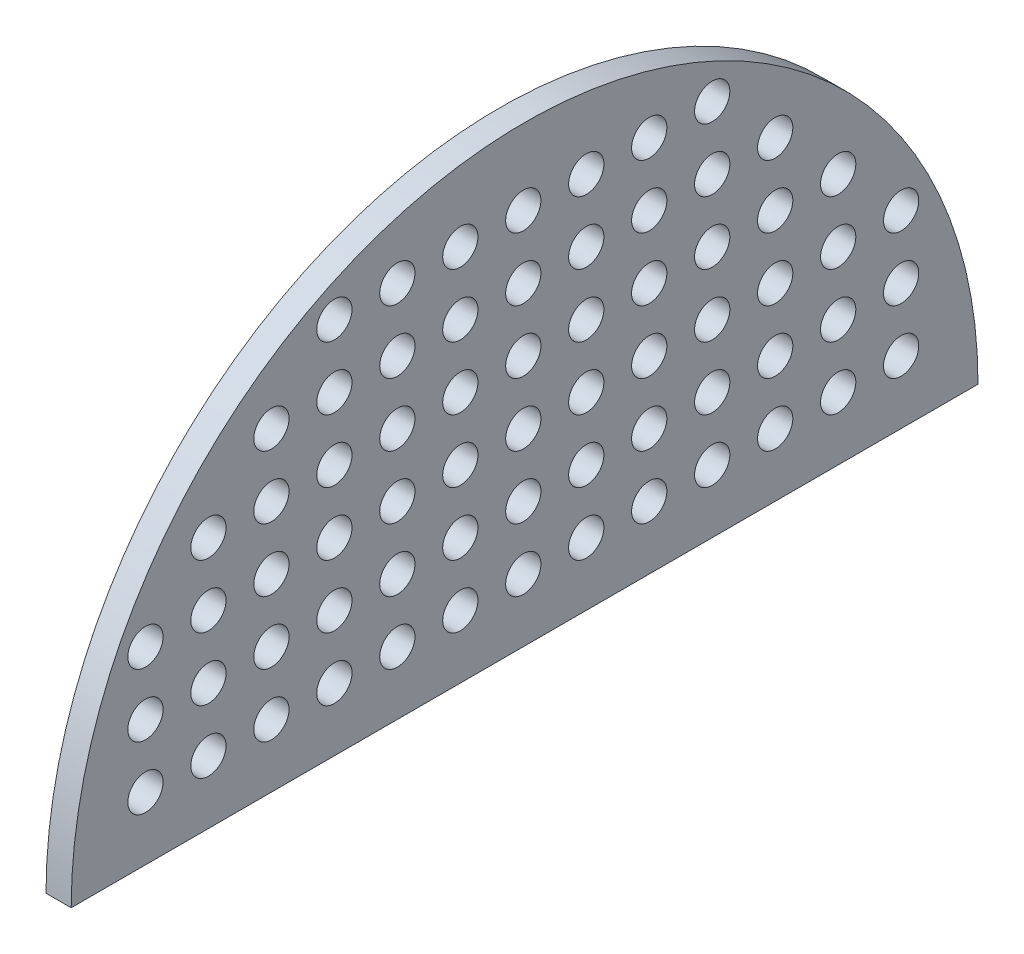
SolidWorks part; units mm, degrees
ref_plane "Front Plane" through (0, 0, 0) normal (0, 0, 1) x (1, 0, 0)
ref_plane "Top Plane" through (0, 0, 0) normal (0, 1, 0) x (1, 0, 0)
ref_plane "Right Plane" through (0, 0, 0) normal (1, 0, 0) x (0, 0, -1)
sketch "Sketch3" plane through (0, 0, 0) normal (1, 0, 0) x (0, 0, -1)
  line L0 (-168.7029, 0) -> (191.2971, 0)
  arc A0 (-168.7029, 0) -> (191.2971, 0) centre (11.2971, 0) cw
  dimension "D1" = 360
extrude "Boss-Extrude2" add sketch "Sketch3" along normal blind 10 contours A0 L0
sketch "Sketch4" plane through (0, 0, 0) normal (-1, 0, 0) x (0, 0, 1)
  line L0 (168.7029, 0) -> (-191.2971, 0) construction
  circle A1 centre (-160.7818, 25) radius 7
  circle A2 centre (-160.7818, 25) radius 10
  circle A3 centre (-135.7818, 25) radius 7
  circle A4 centre (-135.7818, 25) radius 10
  circle A5 centre (-110.7818, 25) radius 7
  circle A6 centre (-110.7818, 25) radius 10
  circle A7 centre (-85.7818, 25) radius 7
  circle A8 centre (-85.7818, 25) radius 10
  circle A9 centre (-60.7818, 25) radius 7
  circle A10 centre (-60.7818, 25) radius 10
  circle A11 centre (-35.7818, 25) radius 7
  circle A12 centre (-35.7818, 25) radius 10
  circle A13 centre (-10.7818, 25) radius 7
  circle A14 centre (-10.7818, 25) radius 10
  circle A15 centre (14.2182, 25) radius 7
  circle A16 centre (14.2182, 25) radius 10
  circle A17 centre (39.2182, 25) radius 7
  circle A18 centre (39.2182, 25) radius 10
  circle A19 centre (64.2182, 25) radius 7
  circle A20 centre (64.2182, 25) radius 10
  circle A21 centre (89.2182, 25) radius 7
  circle A22 centre (89.2182, 25) radius 10
  circle A23 centre (114.2182, 25) radius 7
  circle A24 centre (114.2182, 25) radius 10
  circle A25 centre (139.2182, 25) radius 7
  circle A26 centre (139.2182, 25) radius 10
  circle A27 centre (-135.7818, 50) radius 7
  circle A28 centre (-135.7818, 50) radius 10
  circle A29 centre (-110.7818, 50) radius 7
  circle A30 centre (-110.7818, 50) radius 10
  circle A31 centre (-85.7818, 50) radius 7
  circle A32 centre (-85.7818, 50) radius 10
  circle A33 centre (-60.7818, 50) radius 7
  circle A34 centre (-60.7818, 50) radius 10
  circle A35 centre (-35.7818, 50) radius 7
  circle A36 centre (-35.7818, 50) radius 10
  circle A37 centre (-10.7818, 50) radius 7
  circle A38 centre (-10.7818, 50) radius 10
  circle A39 centre (14.2182, 50) radius 7
  circle A40 centre (14.2182, 50) radius 10
  circle A41 centre (39.2182, 50) radius 7
  circle A42 centre (39.2182, 50) radius 10
  circle A43 centre (64.2182, 50) radius 7
  circle A44 centre (64.2182, 50) radius 10
  circle A45 centre (89.2182, 50) radius 7
  circle A46 centre (89.2182, 50) radius 10
  circle A47 centre (114.2182, 50) radius 7
  circle A48 centre (114.2182, 50) radius 10
  circle A49 centre (139.2182, 50) radius 7
  circle A50 centre (139.2182, 50) radius 10
  circle A51 centre (-135.7818, 75) radius 7
  circle A52 centre (-135.7818, 75) radius 10
  circle A53 centre (-110.7818, 75) radius 7
  circle A54 centre (-110.7818, 75) radius 10
  circle A55 centre (-85.7818, 75) radius 7
  circle A56 centre (-85.7818, 75) radius 10
  circle A57 centre (-60.7818, 75) radius 7
  circle A58 centre (-60.7818, 75) radius 10
  circle A59 centre (-35.7818, 75) radius 7
  circle A60 centre (-35.7818, 75) radius 10
  circle A61 centre (-10.7818, 75) radius 7
  circle A62 centre (-10.7818, 75) radius 10
  circle A63 centre (14.2182, 75) radius 7
  circle A64 centre (14.2182, 75) radius 10
  circle A65 centre (39.2182, 75) radius 7
  circle A66 centre (39.2182, 75) radius 10
  circle A67 centre (64.2182, 75) radius 7
  circle A68 centre (64.2182, 75) radius 10
  circle A69 centre (89.2182, 75) radius 7
  circle A70 centre (89.2182, 75) radius 10
  circle A71 centre (114.2182, 75) radius 7
  circle A72 centre (114.2182, 75) radius 10
  circle A73 centre (139.2182, 75) radius 7
  circle A74 centre (139.2182, 75) radius 10
  circle A75 centre (-135.7818, 100) radius 7
  circle A76 centre (-135.7818, 100) radius 10
  circle A77 centre (-110.7818, 100) radius 7
  circle A78 centre (-110.7818, 100) radius 10
  circle A79 centre (-85.7818, 100) radius 7
  circle A80 centre (-85.7818, 100) radius 10
  circle A81 centre (-60.7818, 100) radius 7
  circle A82 centre (-60.7818, 100) radius 10
  circle A83 centre (-35.7818, 100) radius 7
  circle A84 centre (-35.7818, 100) radius 10
  circle A85 centre (-10.7818, 100) radius 7
  circle A86 centre (-10.7818, 100) radius 10
  circle A87 centre (14.2182, 100) radius 7
  circle A88 centre (14.2182, 100) radius 10
  circle A89 centre (39.2182, 100) radius 7
  circle A90 centre (39.2182, 100) radius 10
  circle A91 centre (64.2182, 100) radius 7
  circle A92 centre (64.2182, 100) radius 10
  circle A93 centre (89.2182, 100) radius 7
  circle A94 centre (89.2182, 100) radius 10
  circle A95 centre (114.2182, 100) radius 7
  circle A96 centre (114.2182, 100) radius 10
  circle A101 centre (-110.7818, 125) radius 7
  circle A102 centre (-110.7818, 125) radius 10
  circle A103 centre (-85.7818, 125) radius 7
  circle A104 centre (-85.7818, 125) radius 10
  circle A105 centre (-60.7818, 125) radius 7
  circle A106 centre (-60.7818, 125) radius 10
  circle A107 centre (-35.7818, 125) radius 7
  circle A108 centre (-35.7818, 125) radius 10
  circle A109 centre (-10.7818, 125) radius 7
  circle A110 centre (-10.7818, 125) radius 10
  circle A111 centre (14.2182, 125) radius 7
  circle A112 centre (14.2182, 125) radius 10
  circle A113 centre (39.2182, 125) radius 7
  circle A114 centre (39.2182, 125) radius 10
  circle A115 centre (64.2182, 125) radius 7
  circle A116 centre (64.2182, 125) radius 10
  circle A117 centre (89.2182, 125) radius 7
  circle A118 centre (89.2182, 125) radius 10
  circle A127 centre (-85.7818, 150) radius 7
  circle A128 centre (-85.7818, 150) radius 10
  circle A129 centre (-60.7818, 150) radius 7
  circle A130 centre (-60.7818, 150) radius 10
  circle A131 centre (-35.7818, 150) radius 7
  circle A132 centre (-35.7818, 150) radius 10
  circle A133 centre (-10.7818, 150) radius 7
  circle A134 centre (-10.7818, 150) radius 10
  circle A135 centre (14.2182, 150) radius 7
  circle A136 centre (14.2182, 150) radius 10
  circle A137 centre (39.2182, 150) radius 7
  circle A138 centre (39.2182, 150) radius 10
  circle A139 centre (64.2182, 150) radius 7
  circle A140 centre (64.2182, 150) radius 10
  circle A147 centre (-160.7818, 50) radius 7
  circle A148 centre (-160.7818, 50) radius 10
  circle A149 centre (-160.7818, 75) radius 7
  circle A150 centre (-160.7818, 75) radius 10
  circle A157 centre (-160.7818, 100) radius 10 [skipped]
  circle A158 centre (-160.7818, 100) radius 7 [skipped]
  circle A159 centre (-160.7818, 125) radius 10 [skipped]
  circle A160 centre (-135.7818, 125) radius 10 [skipped]
  circle A161 centre (-135.7818, 125) radius 7 [skipped]
  circle A162 centre (-135.7818, 150) radius 10 [skipped]
  circle A163 centre (-135.7818, 150) radius 7 [skipped]
  circle A164 centre (-160.7818, 150) radius 10 [skipped]
  circle A165 centre (-160.7818, 150) radius 7 [skipped]
  circle A166 centre (-160.7818, 125) radius 7 [skipped]
  circle A167 centre (-110.7818, 150) radius 10 [skipped]
  circle A168 centre (-110.7818, 150) radius 7 [skipped]
  circle A169 centre (89.2182, 150) radius 10 [skipped]
  circle A170 centre (89.2182, 150) radius 7 [skipped]
  circle A171 centre (114.2182, 150) radius 10 [skipped]
  circle A172 centre (114.2182, 125) radius 10 [skipped]
  circle A173 centre (114.2182, 125) radius 7 [skipped]
  circle A174 centre (139.2182, 125) radius 10 [skipped]
  circle A175 centre (139.2182, 125) radius 7 [skipped]
  circle A176 centre (139.2182, 100) radius 10 [skipped]
  circle A177 centre (139.2182, 100) radius 7 [skipped]
  circle A178 centre (139.2182, 150) radius 10 [skipped]
  circle A179 centre (139.2182, 150) radius 7 [skipped]
  circle A180 centre (114.2182, 150) radius 7 [skipped]
  dimension "D1" = 20
  dimension "D2" = 3
  dimension "D3" = 25
  dimension "D4" = 13
  dimension "D5" = 6
extrude "Cut-Extrude2" cut sketch "Sketch4" against normal blind 10 contours A7 | A5 | A3 | A1 | A13 | A11 | A9 | A15 | A17 | A27 | A19 | A21 | A23 | A25 | A35 | A37 | A33 | A31 | A29 | A39 | A41 | A43 | A45 | A47 | A49 | A59 | A57 | A55 | A53 | A51 | A61 | A63 | A65 | A67 | A69 | A71 | A81 | A79 | A77 | A73 | A75 | A85 | A83 | A87 | A89 | A91 | A103 | A93 | A95 | A101 | A105 | A107 | A109 | A111 | A113 | A115 | A117 | A135 | A133 | A131 | A129 | A127 | A139 | A137 | A149 | A147
